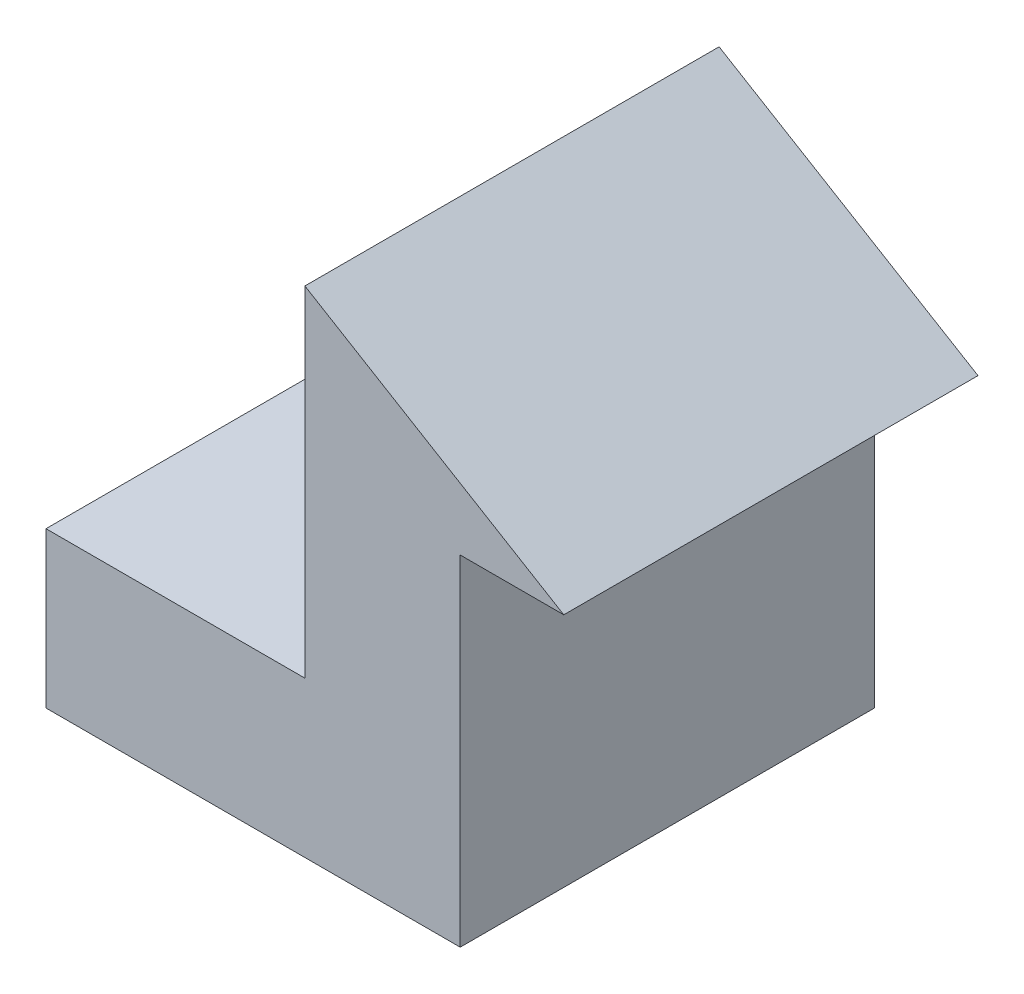
SolidWorks part; units mm, degrees
ref_plane "Plan de face" through (0, 0, 0) normal (0, 0, 1) x (1, 0, 0)
ref_plane "Plan de dessus" through (0, 0, 0) normal (0, 1, 0) x (1, 0, 0)
ref_plane "Plan de droite" through (0, 0, 0) normal (1, 0, 0) x (0, 0, -1)
sketch "Esquisse1" plane through (0, 0, 0) normal (0, 0, 1) x (1, 0, 0)
  line L0 (25, 47.8) -> (50, 32.8)
  line L1 (0, 0) -> (40, 0)
  line L2 (0, 0) -> (0, 15)
  line L3 (0, 15) -> (40, 15)
  line L4 (40, 0) -> (40, 15)
  line L5 (25, 0) -> (40, 0)
  line L6 (25, 0) -> (25, 32.8)
  line L7 (25, 32.8) -> (40, 32.8)
  line L8 (40, 0) -> (40, 32.8)
  line L9 (25, 32.8) -> (50, 32.8)
  line L10 (25, 32.8) -> (25, 47.8)
  line L11 (25, 47.8) -> (50, 47.8)
  line L12 (50, 32.8) -> (50, 47.8)
  dimension "D1" = 15
  dimension "D2" = 17.8
  dimension "D3" = 40
  dimension "D4" = 25
extrude "Boss.-Extru.1" add sketch "Esquisse1" along normal blind 40 contours L1 L6 L3 L2 | L6 L1 L4 L3 | L10 L7 L9 L0
